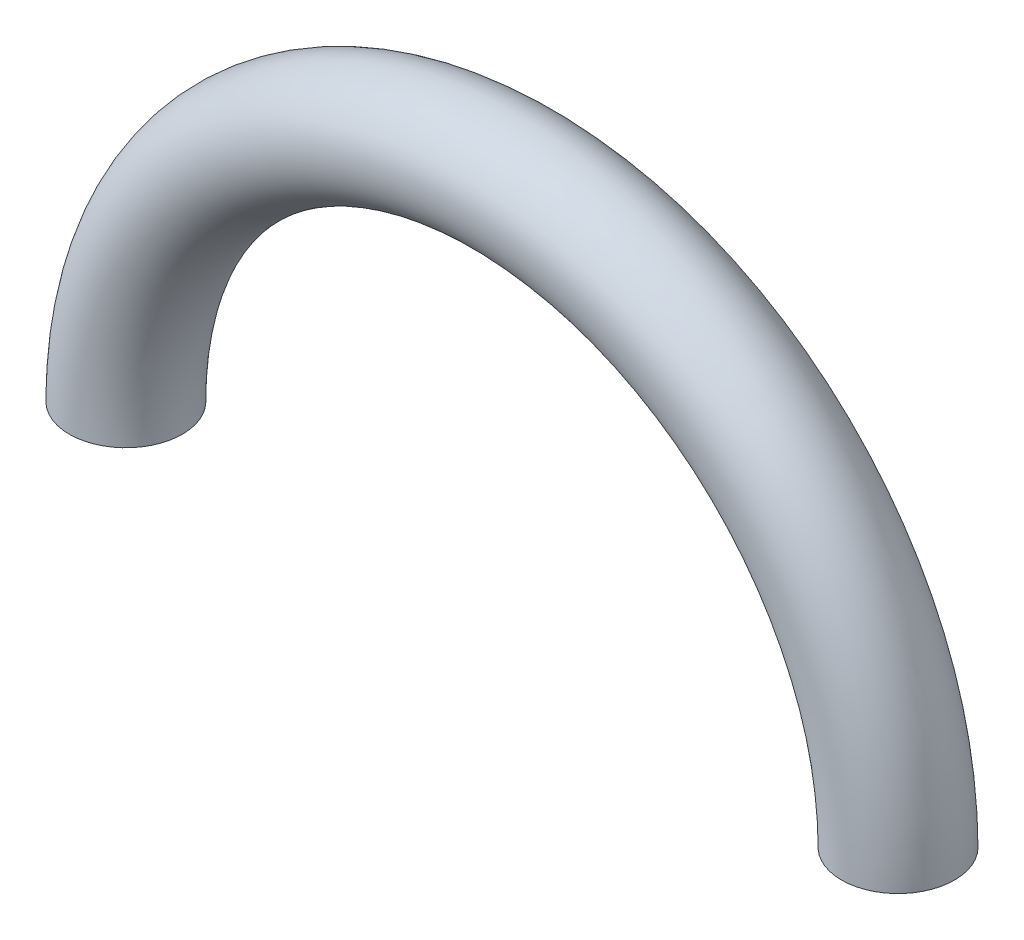
SolidWorks part; units mm, degrees
ref_plane "Front Plane" through (0, 0, 0) normal (0, 0, 1) x (1, 0, 0)
ref_plane "Top Plane" through (0, 0, 0) normal (0, 1, 0) x (1, 0, 0)
ref_plane "Right Plane" through (0, 0, 0) normal (1, 0, 0) x (0, 0, -1)
sketch "Sketch6" plane through (0, 0, 0) normal (0, 0, 1) x (1, 0, 0)
  arc A0 (12.4999, 0) -> (-12.4999, 0) centre (0, 0) ccw
sketch "Sketch7" plane through (0, 0, 0) normal (0, 1, 0) x (1, 0, 0)
  line L0 (-12.4999, 0) -> (12.4999, 0) construction
  circle A0 centre (12.4999, 0) radius 1.8305
sweep "Sweep2" add profiles "Sketch7" path "Sketch6"
